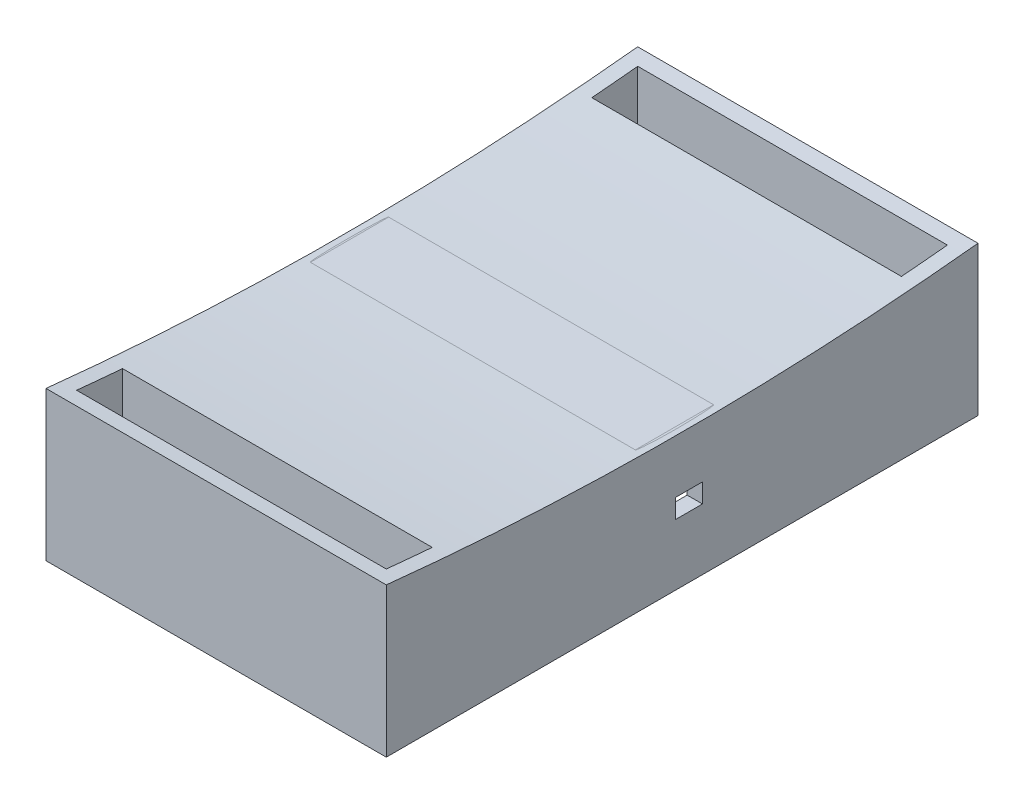
SolidWorks part; units mm, degrees
ref_plane "Front Plane" through (0, 0, 0) normal (0, 0, 1) x (1, 0, 0)
ref_plane "Top Plane" through (0, 0, 0) normal (0, 1, 0) x (1, 0, 0)
ref_plane "Right Plane" through (0, 0, 0) normal (1, 0, 0) x (0, 0, -1)
sketch "Sketch1" plane through (0, 0, 0) normal (0, 1, 0) x (1, 0, 0)
  line L5 (-15.23, -20.155) -> (15.23, -20.155) construction
  line L6 (15.23, 20.155) -> (15.23, -20.155) construction
  line L7 (-15.23, 20.155) -> (15.23, 20.155) construction
  line L8 (-15.23, 20.155) -> (-15.23, -20.155) construction
  circle A0 centre (-12.92, 17.845) radius 1 construction
  circle A1 centre (11.5, 17.845) radius 1 construction
  circle A2 centre (11.5, -18.155) radius 1 construction
  dimension "D5" = 2.31
  dimension "D7" = 2.31
  dimension "D9" = 2
  dimension "D10" = 2
  dimension "D11" = 3.73
  dimension "D13" = 2
  dimension "D1" = 30.46
  dimension "D2" = 40.31
  dimension "D3" = 15.23
  dimension "D4" = 20.155
  dimension "D6" = 2.31
  dimension "D8" = 3.73
  dimension "D12" = 2
sketch "Sketch2" plane through (0, 0, 0) normal (0, 1, 0) x (1, 0, 0)
  line L0 (-15.23, -20.155) -> (15.23, -20.155) construction
  line L1 (-20.23, 25.155) -> (20.23, 25.155)
  line L2 (-20.23, 25.155) -> (-20.23, -30.155)
  line L3 (-20.23, -30.155) -> (20.23, -30.155)
  line L4 (20.23, 25.155) -> (20.23, -30.155)
  line L5 (-15.23, 20.155) -> (15.23, 20.155) construction
  line L6 (-15.23, 20.155) -> (-15.23, -20.155) construction
  line L7 (15.23, 20.155) -> (15.23, -20.155) construction
  dimension "D1" = 10
  dimension "D2" = 5
  dimension "D3" = 5
  dimension "D4" = 5
extrude "Boss-Extrude1" add sketch "Sketch2" along normal blind 2
sketch "Sketch3" plane through (0, 0, 0) normal (0, -1, 0) x (1, 0, 0)
  circle A1 centre (-12.92, -17.845) radius 1.5
  circle A2 centre (11.5, -17.845) radius 1.5
  circle A4 centre (-12.92, -17.845) radius 4
  circle A5 centre (11.5, -17.845) radius 4
  dimension "D1" = 3
  dimension "D2" = 8
  dimension "D3" = 3
  dimension "D4" = 8
extrude "Boss-Extrude2" add sketch "Sketch3" along normal blind 4
fillet "Fillet1" radius 2 2 edges at (-12.92, 0, -13.845) (11.5, 0, -13.845)
sketch "Sketch6" plane through (0, 2, 0) normal (0, 1, 0) x (1, 0, 0)
  line L0 (-20.23, 25.155) -> (-20.23, -30.155) construction
  line L1 (20.23, 25.155) -> (-20.23, 25.155) construction
  line L2 (20.23, -30.155) -> (20.23, 25.155) construction
  line L3 (-20.23, -30.155) -> (20.23, -30.155) construction
  line L4 (-20.23, 25.155) -> (-20.23, -30.155)
  line L5 (20.23, 25.155) -> (-20.23, 25.155)
  line L6 (20.23, -30.155) -> (20.23, 25.155)
  line L7 (-20.23, -30.155) -> (20.23, -30.155)
  line L8 (22.23, 27.155) -> (-22.23, 27.155)
  line L9 (-22.23, 27.155) -> (-22.23, -32.155)
  line L10 (-22.23, -32.155) -> (22.23, -32.155)
  line L11 (22.23, -32.155) -> (22.23, 27.155)
  dimension "D1" = 2
extrude "Boss-Extrude3" add sketch "Sketch6" against normal blind 17.5
sketch "Sketch9" plane through (0, 0, 30.155) normal (0, 0, -1) x (-1, 0, 0)
  line L0 (22.23, -15.5) -> (-22.23, -15.5) construction
  line L1 (-22.23, -15.5) -> (-22.23, 2) construction
  line L2 (20.23, -10.5) -> (20.98, -10.5)
  line L3 (20.23, -15.5) -> (20.23, -10.5)
  line L4 (20.23, -15.5) -> (20.98, -15.5)
  line L5 (0, 0) -> (0, -28.4666) construction
  line L6 (20.98, -10.5) -> (20.98, -15.5)
  line L7 (-20.98, -10.5) -> (-20.98, -15.5)
  line L8 (-20.23, -15.5) -> (-20.98, -15.5)
  line L9 (-20.23, -15.5) -> (-20.23, -10.5)
  line L10 (-20.23, -10.5) -> (-20.98, -10.5)
  dimension "D1" = 0
  dimension "D2" = 5
  dimension "D3" = 5
  dimension "D4" = 0.75
  dimension "D5" = 0.75
  dimension "D6" = 1.25
sweep "Cut-Sweep1" cut profiles "Sketch9" path edge at (-20.23, -15.5, 2.5)
sketch "Sketch10" plane through (0, -15.5, 0) normal (0, -1, 0) x (1, 0, 0)
  line L1 (-20.23, 30.155) -> (20.23, 30.155) construction
  line L2 (-23.461, 0) -> (26.9234, 0) construction
  line L3 (-20.23, 30.155) -> (20.23, 30.155)
  line L4 (-20.23, 30.155) -> (-20.98, 30.155)
  line L5 (-20.98, 30.155) -> (-20.98, 30.905)
  line L6 (-20.98, 30.905) -> (20.98, 30.905)
  line L7 (20.98, 30.905) -> (20.98, 30.155)
  line L8 (20.98, 30.155) -> (20.23, 30.155)
  line L9 (20.23, -25.155) -> (-20.23, -25.155) construction
  line L10 (20.23, -25.155) -> (-20.23, -25.155)
  line L11 (-20.23, -25.155) -> (-20.98, -25.155)
  line L12 (-20.98, -25.155) -> (-20.98, -25.905)
  line L13 (-20.98, -25.905) -> (20.98, -25.905)
  line L14 (20.98, -25.905) -> (20.98, -25.155)
  line L15 (20.98, -25.155) -> (20.23, -25.155)
  dimension "D1" = 0.75
  dimension "D2" = 0.75
extrude "Cut-Extrude1" cut sketch "Sketch10" against normal blind 5
fillet "Fillet3" radius 1 16 edges at (22.23, -6.75, 32.155) (22.23, -6.75, -27.155) (-22.23, -6.75, -27.155) (-22.23, -6.75, 32.155) (0, 2, -27.155) (22.23, 2, 2.5) (0, 2, 32.155) (-22.23, 2, 2.5) (0, 0, 30.155) (-20.23, 0, 2.5) (0, 0, -25.155) (20.23, 0, 2.5)
fillet "Fillet4" radius 0.5 4 edges at (-20.98, -13, 30.905) (-20.98, -13, -25.905) (20.98, -13, -25.905) (20.98, -13, 30.905)
sketch "Sketch11" plane through (0, 0, -27.155) normal (0, 0, -1) x (-1, 0, 0)
  line L0 (22.23, 1) -> (22.23, -15.5) construction
  line L1 (9.73, -9) -> (7.73, -9)
  line L2 (9.73, -9) -> (9.73, -7)
  line L3 (9.73, -7) -> (7.73, -7)
  line L4 (7.73, -9) -> (7.73, -7)
  line L5 (-21.23, 2) -> (21.23, 2) construction
  dimension "D1" = 12.5
  dimension "D2" = 2
  dimension "D3" = 2
  dimension "D4" = 9
sketch "Sketch12" plane through (0, 2, 0) normal (0, 1, 0) x (1, 0, 0)
  line L0 (-22.23, 26.155) -> (-22.23, 36.155)
  line L1 (-22.23, 36.155) -> (22.23, 36.155)
  line L2 (22.23, 36.155) -> (22.23, 26.155)
  line L3 (-22.23, 26.155) -> (22.23, 26.155)
  line L4 (-21.23, 0) -> (29.0707, 0) construction
  line L5 (-21.23, 26.155) -> (-21.23, -31.155) construction
  line L6 (-22.23, -31.155) -> (22.23, -31.155)
  line L7 (22.23, -41.155) -> (22.23, -31.155)
  line L8 (-22.23, -41.155) -> (22.23, -41.155)
  line L9 (-22.23, -31.155) -> (-22.23, -41.155)
  line L10 (-21.23, -31.155) -> (21.23, -31.155) construction
  line L11 (-20.23, -39.155) -> (20.23, -39.155)
  line L12 (20.23, -39.155) -> (20.23, -33.155)
  line L13 (-20.23, -33.155) -> (20.23, -33.155)
  line L14 (-20.23, -33.155) -> (-20.23, -39.155)
  line L15 (-20.23, 34.155) -> (20.23, 34.155)
  line L16 (20.23, 34.155) -> (20.23, 28.155)
  line L17 (-20.23, 28.155) -> (20.23, 28.155)
  line L18 (-20.23, 28.155) -> (-20.23, 34.155)
  dimension "D1" = 10
  dimension "D2" = 44.46
  dimension "D3" = 44.46
  dimension "D4" = 10
  dimension "D5" = 0
  dimension "D6" = 10
  dimension "D7" = 44.46
  dimension "D9" = 57.31
  dimension "D10" = 2
  dimension "D11" = 61.31
  dimension "D8" = 2
extrude "Boss-Extrude4" add sketch "Sketch12" against normal blind 8
fillet "Fillet5" radius 1 4 edges at (-22.23, 2, 36.155) (-22.23, 2, -31.155) (22.23, 2, 36.155) (22.23, 2, -31.155)
extrude "Cut-Extrude2" cut sketch "Sketch11" against normal blind 8 and the other way blind 10
sketch "Sketch13" plane through (22.23, 0, 0) normal (1, 0, 0) x (0, 0, -1)
  line L0 (27.155, -6) -> (27.155, -15.5) construction
  line L1 (0.155, -7.5) -> (-3.345, -7.5)
  line L2 (0.155, -7.5) -> (0.155, -5)
  line L3 (0.155, -5) -> (-3.345, -5)
  line L4 (-3.345, -7.5) -> (-3.345, -5)
  line L6 (18.845, 0) -> (16.845, 0) construction
  dimension "D1" = 2.5
  dimension "D2" = 3.5
  dimension "D3" = 27
  dimension "D4" = 3.5
  dimension "D5" = 5
extrude "Cut-Extrude3" cut sketch "Sketch13" against normal blind 8
sketch "Sketch14" plane through (22.23, 0, 0) normal (1, 0, 0) x (0, 0, -1)
  line L2 (36.155, 4) -> (36.155, 1)
  line L3 (36.155, 1) -> (-41.155, 1)
  line L4 (-41.155, 1) -> (-41.155, 4)
  arc A0 (36.155, 4) -> (-41.155, 4) centre (-2.5, 370.0157) cw
  dimension "D1" = 368.0512
  dimension "D2" = 3
  dimension "D3" = 3
extrude "Boss-Extrude5" add sketch "Sketch14" against normal up to surface (44.46 mm away) up to face at (-22.23, -5.1, 2.5)
sketch "Sketch16" plane through (0, -6, 0) normal (0, -1, 0) x (1, 0, 0)
  line L0 (-20.23, 39.155) -> (20.23, 39.155) construction
  line L1 (20.23, 39.155) -> (20.23, 33.155) construction
  line L2 (20.23, 33.155) -> (-20.23, 33.155) construction
  line L3 (-20.23, 33.155) -> (-20.23, 39.155) construction
  line L4 (-20.23, -34.155) -> (-20.23, -28.155) construction
  line L5 (20.23, -34.155) -> (-20.23, -34.155) construction
  line L6 (20.23, -28.155) -> (20.23, -34.155) construction
  line L7 (-20.23, -28.155) -> (20.23, -28.155) construction
  line L8 (-20.23, 39.155) -> (20.23, 39.155)
  line L9 (20.23, 39.155) -> (20.23, 33.155)
  line L10 (20.23, 33.155) -> (-20.23, 33.155)
  line L11 (-20.23, 33.155) -> (-20.23, 39.155)
  line L12 (-20.23, -34.155) -> (-20.23, -28.155)
  line L13 (20.23, -34.155) -> (-20.23, -34.155)
  line L14 (20.23, -28.155) -> (20.23, -34.155)
  line L15 (-20.23, -28.155) -> (20.23, -28.155)
extrude "Cut-Extrude4" cut sketch "Sketch16" against normal through all both and the other way through all
sketch "Sketch19" plane through (0, -6, 0) normal (0, -1, 0) x (1, 0, 0)
  line L1 (-20.23, -34.155) -> (20.23, -34.155)
  line L2 (-20.23, -34.155) -> (-20.23, -28.155)
  line L3 (-20.23, -28.155) -> (20.23, -28.155)
  line L4 (20.23, -34.155) -> (20.23, -28.155)
  line L5 (-22.23, -36.155) -> (22.23, -36.155)
  line L6 (-22.23, -36.155) -> (-22.23, -26.155)
  line L7 (-22.23, -26.155) -> (22.23, -26.155)
  line L8 (22.23, -36.155) -> (22.23, -26.155)
  line L9 (22.23, 31.155) -> (-22.23, 31.155)
  line L10 (22.23, 31.155) -> (22.23, 41.155)
  line L11 (22.23, 41.155) -> (-22.23, 41.155)
  line L12 (-22.23, 31.155) -> (-22.23, 41.155)
  line L13 (-20.23, 33.155) -> (20.23, 33.155)
  line L14 (-20.23, 33.155) -> (-20.23, 39.155)
  line L15 (-20.23, 39.155) -> (20.23, 39.155)
  line L16 (20.23, 33.155) -> (20.23, 39.155)
extrude "Boss-Extrude7" add sketch "Sketch19" along normal blind 9.5
sketch "Sketch20" plane through (0, 0, -26.155) normal (0, 0, 1) x (1, 0, 0)
  line L4 (-9.73, -7) -> (-9.73, -9)
  line L5 (-9.73, -9) -> (-7.73, -9)
  line L6 (-7.73, -9) -> (-7.73, -7)
  line L7 (-7.73, -7) -> (-9.73, -7)
  line L8 (-9.73, -7) -> (-9.73, -9)
  line L9 (-9.73, -9) -> (-7.73, -9)
  line L10 (-7.73, -9) -> (-7.73, -7)
  line L11 (-7.73, -7) -> (-9.73, -7)
  dimension "D1" = 0
extrude "Cut-Extrude5" cut sketch "Sketch20" against normal blind 5
